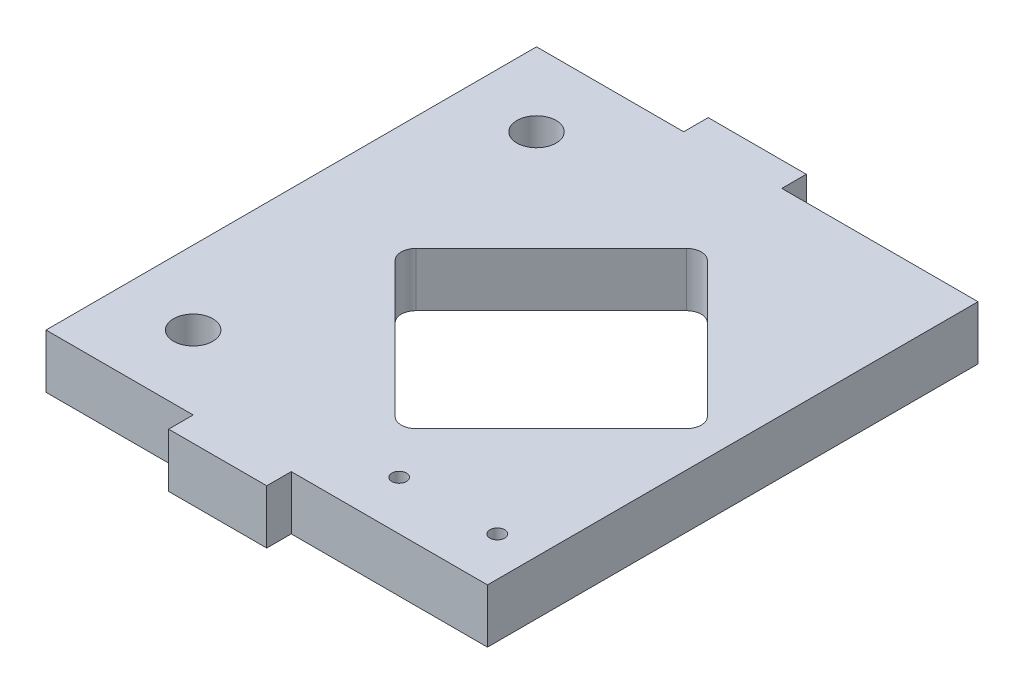
SolidWorks part; units mm, degrees
ref_plane "Front Plane" through (0, 0, 0) normal (0, 0, 1) x (1, 0, 0)
ref_plane "Top Plane" through (0, 0, 0) normal (0, 1, 0) x (1, 0, 0)
ref_plane "Right Plane" through (0, 0, 0) normal (1, 0, 0) x (0, 0, -1)
sketch "Sketch1" plane through (0, 0, 0) normal (0, 1, 0) x (1, 0, 0)
  line L0 (0, 50) -> (40, 50)
  line L1 (-40, 50) -> (-20, 50)
  line L2 (-40, 50) -> (-40, -50) construction
  line L3 (-40, -50) -> (-20, -50)
  line L4 (40, 50) -> (40, -50)
  line L5 (-40, 50) -> (40, -50) construction
  line L6 (-40, -50) -> (40, 50) construction
  line L8 (0, 50) -> (0, 55)
  line L9 (0, 55) -> (-20, 55)
  line L10 (-20, 50) -> (-20, 55)
  line L11 (-55, 0) -> (55, 0) construction
  line L12 (-20, -50) -> (-20, -55)
  line L13 (0, -55) -> (-20, -55)
  line L14 (0, -50) -> (0, -55)
  line L15 (0, -50) -> (40, -50)
  line L16 (0, 0) -> (-35, 0) construction
  line L17 (-40, 50) -> (-50, 50)
  line L18 (-50, 50) -> (-50, -50)
  line L19 (-50, -50) -> (-40, -50)
  line L20 (-35, 0) -> (-35, 35) construction
  circle A2 centre (-35, 35) radius 4
  circle A3 centre (-35, -35) radius 4
  point P0 (0, 0)
  dimension "D8" = 8
  dimension "D1" = 100
  dimension "D2" = 80
  dimension "D3" = 5
  dimension "D4" = 20
  dimension "D5" = 35
  dimension "D6" = 10
  dimension "D7" = 35
extrude "Boss-Extrude1" add sketch "Sketch1" along normal blind 11
sketch "Sketch2" plane through (0, 11, 0) normal (0, 1, 0) x (1, 0, 0)
  line L0 (-50, 0) -> (22, 0) construction
  line L1 (-50, 50) -> (-50, -50) construction
  line L2 (22, 0) -> (22, -40) construction
  line L3 (22, -40) -> (32, -40) construction
  circle A0 centre (32, -40) radius 1.5
  circle A1 centre (12, -40) radius 1.5
  dimension "D2" = 40
  dimension "D4" = 3
  dimension "D1" = 72
  dimension "D3" = 10
extrude "Cut-Extrude1" cut sketch "Sketch2" against normal blind 10
sketch "Sketch3" plane through (0, 11, 0) normal (0, 1, 0) x (1, 0, 0)
  line L0 (40, 0) -> (3, 0) construction
  line L1 (40, -50) -> (40, 50) construction
  line L3 (-28.8198, 0) -> (3, -31.8198)
  line L4 (3, -31.8198) -> (34.8198, 0)
  line L5 (34.8198, 0) -> (3, 31.8198)
  line L6 (3, 31.8198) -> (-28.8198, 0)
  circle A0 centre (3, 0) radius 22.5 construction
  dimension "D1" = 37
extrude "Cut-Extrude2" cut sketch "Sketch3" against normal blind 11
fillet "Fillet1" radius 3 4 edges at (3, 5.5, -31.8198) (-28.8198, 5.5, 0) (3, 5.5, 31.8198) (34.8198, 5.5, 0)
